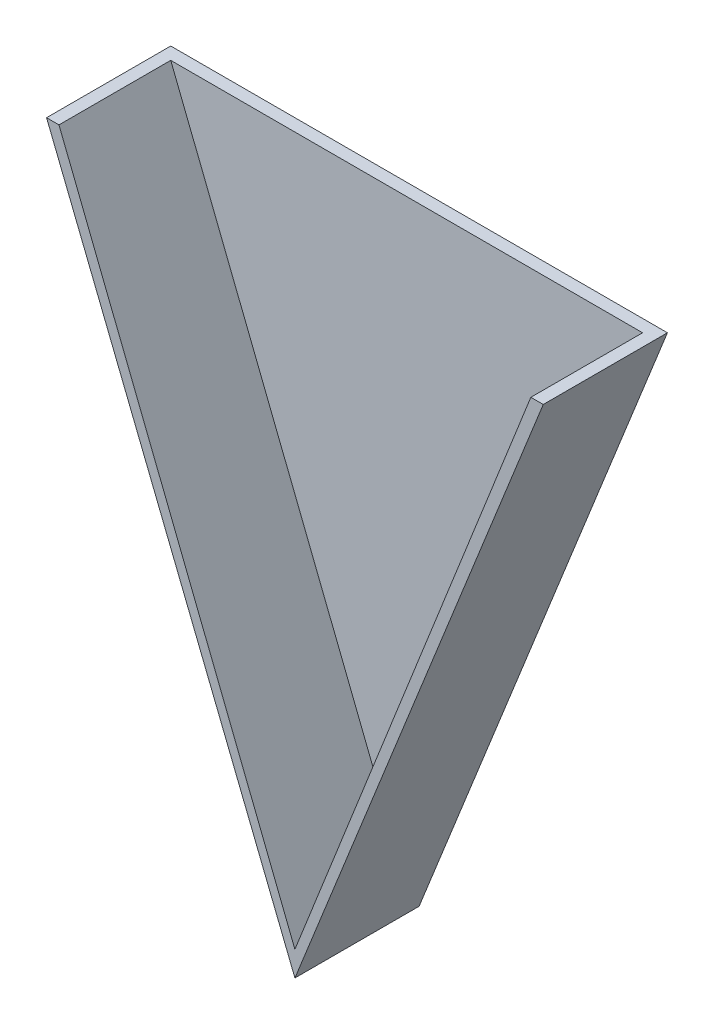
SolidWorks part; units mm, degrees
ref_plane "Front Plane" through (0, 0, 0) normal (0, 0, 1) x (1, 0, 0)
ref_plane "Top Plane" through (0, 0, 0) normal (0, 1, 0) x (1, 0, 0)
ref_plane "Right Plane" through (0, 0, 0) normal (1, 0, 0) x (0, 0, -1)
ref_plane "Plane1" through (0, 0, 0) normal (0, 0, 1) x (1, 0, 0)
sketch "Sketch1" plane through (0, 0, 0) normal (0, 0, 1) x (1, 0, 0)
  line L0 (-0.508, 0) -> (0, -1.27)
  line L1 (0, -1.27) -> (0.508, 0)
  line L2 (0.508, 0) -> (-0.508, 0)
extrude "Boss-Extrude1" add sketch "Sketch1" against normal blind 0.254
ref_plane "Plane2" through (0, 0, -0.2286) normal (0, 0, 1) x (1, 0, 0)
sketch "Sketch2" plane through (0, 0, -0.2286) normal (0, 0, 1) x (1, 0, 0)
  line L0 (-0.4826, 0) -> (0, -1.2192)
  line L1 (0, -1.2192) -> (0.4826, 0)
  line L2 (0.4826, 0) -> (-0.4826, 0)
extrude "Cut-Extrude1" cut sketch "Sketch2" along normal blind 0.2794
